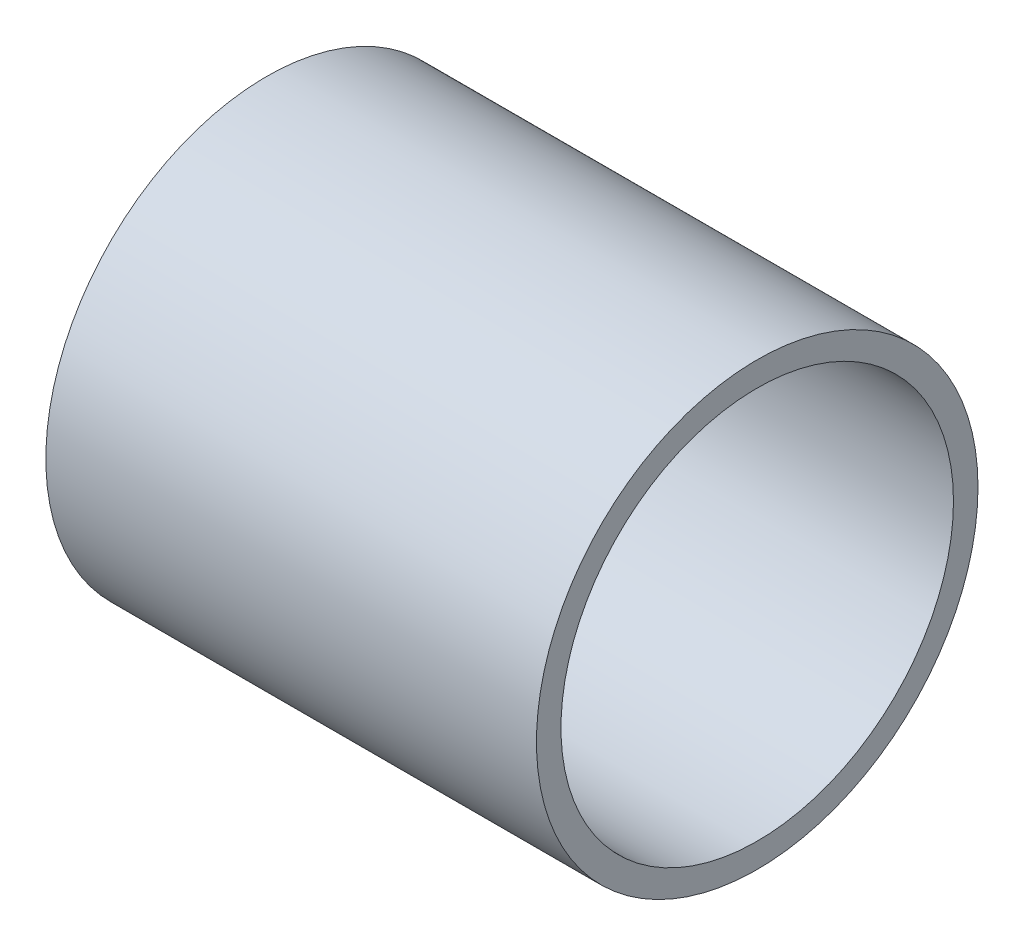
SolidWorks part; units mm, degrees
ref_plane "Front Plane" through (0, 0, 0) normal (0, 0, 1) x (1, 0, 0)
ref_plane "Top Plane" through (0, 0, 0) normal (0, 1, 0) x (1, 0, 0)
ref_plane "Right Plane" through (0, 0, 0) normal (1, 0, 0) x (0, 0, -1)
sketch "Sketch2" plane through (0, 0, 0) normal (1, 0, 0) x (0, 0, -1)
  circle A0 centre (0, 0) radius 2.25
  circle A1 centre (0, 0) radius 2
  dimension "D1" = 4
  dimension "D2" = 4.5
extrude "Boss-Extrude1" add sketch "Sketch2" along normal blind 5
